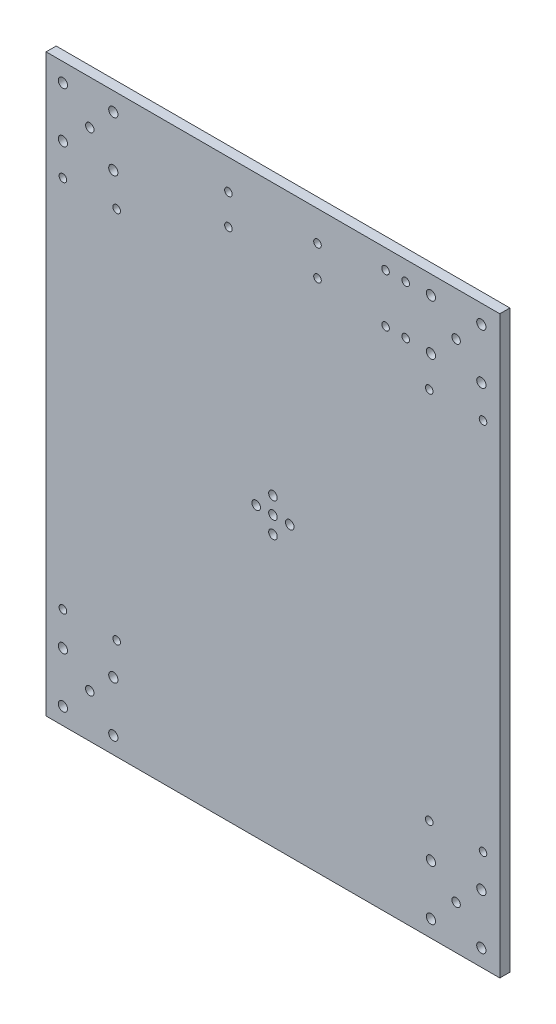
SolidWorks part; units mm, degrees
ref_plane "Спереди" through (0, 0, 0) normal (0, 0, 1) x (1, 0, 0)
ref_plane "Сверху" through (0, 0, 0) normal (0, 1, 0) x (1, 0, 0)
ref_plane "Справа" through (0, 0, 0) normal (1, 0, 0) x (0, 0, -1)
sketch "Эскиз3" plane through (0, 0, 0) normal (0, 0, 1) x (1, 0, 0)
  line L0 (0, 0) -> (0, 10) construction
  line L5 (135, -171.15) -> (-135, -171.15)
  line L6 (135, -171.15) -> (135, 171.15)
  line L7 (135, 171.15) -> (-135, 171.15)
  line L8 (-135, -171.15) -> (-135, 171.15)
  line L9 (0, 0) -> (10, 0) construction
  line L10 (0, 0) -> (0, -10) construction
  line L11 (0, 0) -> (-10, 0) construction
  line L12 (79, 130.65) -> (79, 159.65) construction
  line L13 (79, 159.65) -> (67, 159.65) construction
  line L14 (67, 159.65) -> (67, 130.65) construction
  line L15 (67, 130.65) -> (79, 130.65) construction
  circle A0 centre (0, 0) radius 2.55
  circle A1 centre (0, 10) radius 2.55
  circle A2 centre (10, 0) radius 2.55
  circle A3 centre (0, -10) radius 2.55
  circle A4 centre (-10, 0) radius 2.55
  circle A17 centre (67, 159.65) radius 2.25
  circle A18 centre (79, 159.65) radius 2.25
  circle A19 centre (67, 130.65) radius 2.25
  circle A20 centre (79, 130.65) radius 2.25
  point P0 (0, 0)
  point P5 (-135, 0)
  point P6 (0, 171.15)
  point P21 (0, 0)
  dimension "D3" = 5.1
  dimension "D4" = 5.1
  dimension "D7" = 4.5
  dimension "D1" = 342.3
  dimension "D2" = 270
  dimension "D5" = 10
  dimension "Позиция_крепления_Z_X" = 67
  dimension "Позиция_крепления_Z_Y" = 159.65
  dimension "Шаг_крепления_Z_X" = 12
  dimension "Шаг_крепления_Z_Y" = 29
  dimension "D6" = 4
extrude "Бобышка-Вытянуть1" add sketch "Эскиз3" along normal blind 6
sketch "Эскиз4" plane through (0, 0, 6) normal (0, 0, 1) x (1, 0, 0)
  line L0 (135, 171.15) -> (-135, 171.15) construction
  line L1 (-135, 171.15) -> (-135, -171.15) construction
  circle A0 centre (-109, 145.15) radius 2.5
  dimension "D1" = 5
  dimension "D2" = 26
  dimension "D3" = 26
extrude "Вырез-Вытянуть1" cut sketch "Эскиз4" against normal through all contours A0
pattern_linear "Линейный массив1" count 2 spacing 218 along (1, 0, 0) count 2 spacing 290.3 along (0, -1, 0) of "Вырез-Вытянуть1"
sketch "Эскиз7" plane through (0, 0, 0) normal (0, 0, -1) x (-1, 0, 0)
  line L9 (-26.5, 153.15) -> (26.5, 153.15) construction
  line L10 (-26.5, 153.15) -> (-26.5, 135.15) construction
  line L11 (-26.5, 135.15) -> (26.5, 135.15) construction
  line L16 (26.5, 153.15) -> (26.5, 135.15) construction
  line L17 (-135, 171.15) -> (135, 171.15) construction
  circle A0 centre (-26.5, 153.15) radius 2.25
  circle A1 centre (26.5, 153.15) radius 2.25
  circle A2 centre (-26.5, 135.15) radius 2.25
  circle A3 centre (26.5, 135.15) radius 2.25
  point P4 (0, 135.15)
  dimension "D4" = 4.5
  dimension "D5" = 4.5
  dimension "D6" = 4.5
  dimension "D7" = 4.5
  dimension "D1" = 53
  dimension "D2" = 18
  dimension "D3" = 18
extrude "Вырез-Вытянуть2" cut sketch "Эскиз7" against normal through all
sketch "Эскиз8" plane through (0, 0, 0) normal (0, 0, -1) x (-1, 0, 0)
  line L0 (93, 111.15) -> (125, 111.15) construction
  line L8 (135, 171.15) -> (135, -171.15) construction
  line L9 (-135, 171.15) -> (135, 171.15) construction
  circle A4 centre (93, 111.15) radius 2.25
  circle A5 centre (125, 111.15) radius 2.25
  dimension "D3" = 32
  dimension "D4" = 10
  dimension "D5" = 60
  dimension "D1" = 4.5
  dimension "D2" = 4.5
extrude "Вырез-Вытянуть3" cut sketch "Эскиз8" against normal through all
pattern_linear "Линейный массив2" count 2 spacing 222.3 along (0, -1, 0) count 2 spacing 218 along (1, 0, 0) of "Вырез-Вытянуть3"
sketch "Эскиз10" plane through (0, 0, 0) normal (0, 0, -1) x (-1, 0, 0)
  line L0 (-124, 130.15) -> (-94, 130.15) construction
  line L1 (-129, 125.15) -> (-89, 125.15) construction
  line L2 (-129, 125.15) -> (-129, 165.15) construction
  line L3 (-129, 165.15) -> (-89, 165.15) construction
  line L4 (-89, 125.15) -> (-89, 165.15) construction
  line L5 (-129, 125.15) -> (-89, 165.15) construction
  line L6 (-129, 165.15) -> (-89, 125.15) construction
  line L8 (-94, 130.15) -> (-94, 160.15) construction
  line L10 (-94, 160.15) -> (-124, 160.15) construction
  circle A0 centre (-124, 160.15) radius 2.75
  circle A1 centre (-94, 160.15) radius 2.75
  circle A2 centre (-94, 130.15) radius 2.75
  circle A3 centre (-124, 130.15) radius 2.75
  point P0 (-109, 145.15)
  dimension "D2" = 5.5
  dimension "D1" = 40
  dimension "D3" = 30
extrude "Вырез-Вытянуть4" cut sketch "Эскиз10" against normal through all
pattern_linear "Линейный массив3" count 2 spacing 219 along (-1, 0, 0) count 2 spacing 291.3 along (0, -1, 0) of "Вырез-Вытянуть4"
equation "\"Ширина груза\"= 160"
equation "\"Глубина груза\"= 240"
equation "\"Высота груза\"= 160"
equation "\"Ширина ячейки\"= \"Ширина груза\" + 10"
equation "\"Глубина ячейки\"= \"Глубина груза\" + 10"
equation "\"Высота ячейки\"= \"Высота груза\" + 10 + 13"
equation "\"Колво ячеек ширина\"= 2"
equation "\"Колво ячеек высота\"= 2"
equation "\"Толщина стенки\" = \"Толщина тонких панелей\""
equation "\"Крепление дверцы\"= 5 "
equation "\"Ширина рейки\"= \"Толщина шестерни\""
equation "\"Высота рейки\"= 20"
equation "\"Высота пола\" = 2*\"Толщина тонких панелей\""
equation "\"Колво полозьев\"= 5"
equation "\"Отступ рейки\"= 20"
equation "\"Глубина каретки\"= \"Глубина ячейки\" + 30 + \"Мотор Y высота корпуса\" + 20"
equation "\"Длинна рейки\" = (\"Ширина ячейки\"+\"Толщина вертикальных стенок\"+\"Крепление дверцы\")*\"Колво ячеек ширина\"+\"Ширина ячейки выгрузки\"*\"Колво выгрузки\"+\"Толщина вертикальных стенок\"+2*\"Отступ крепления мотора фиксации\"-\"Крепление дверцы\"*\"Колво ячеек ширина\""
equation "\"Отступ шпильки\"= 26"
equation "\"Диаметр шпильки\"= 5"
equation "\"D1@Бобышка-Вытянуть1\" = \"Толщина стенки\""
equation "\"D1@Эскиз4\"= \"Диаметр шпильки\""
equation "\"D2@Эскиз4\"=\"Отступ шпильки\""
equation "\"D3@Эскиз4\"= \"Отступ шпильки\""
equation "\"D2@Эскиз3\"=\"Ширина ячейки\" + \"Ширина пластины\" * 2"
equation "\"D1@Эскиз3\"=\"Глубина каретки\" "
equation "\"D3@Линейный массив1\"=\"Ширина ячейки\"  +\"Ширина пластины\" *2 - \"Отступ шпильки\" * 2"
equation "\"D4@Линейный массив1\"=\"Глубина каретки\" + \"Ширина рейки\" * 2 - \"Отступ шпильки\" * 2 - \"Ширина рейки\" * 2"
equation "\"Длинна шпильки\" = (\"Высота ячейки\"+\"Толщина горизонтальных плит\"+\"Высота пола\")*\"Колво ячеек высота\"+2*(\"Толщина горизонтальных плит\"+\"Отступ рейки\")"
equation "\"Ширина пластины\"= 50  "
equation "\"Высота зона выгрузки\"= \"Высота ячейки\" * 2 + \"Толщина стенки\" * 2"
equation "\"Колво выгрузки\"= 1"
equation "\"Отступ крепления мотора фиксации\" = (\"Ширина пластины\"+20-\"Толщина вертикальных стенок\")/2"
equation "\"Мотор X ширина корпуса\"= 42.3"
equation "\"Мотор X высота корпуса\"= 42.3"
equation "\"Мотор X длина корпуса\"= 40"
equation "\"Мотор X вылет вала\"= 19.8"
equation "\"Мотор Y ширина корпуса\"= 42.3"
equation "\"Мотор Y высота корпуса\"= 42.3"
equation "\"Мотор Y длина корпуса\"= 48"
equation "\"Мотор Y вылет вала\"= 30"
equation "\"Мотор Z ширина корпуса\"= 42"
equation "\"Мотор Z высота корпуса\"= 42"
equation "\"Мотор Z длина корпуса\"= 40"
equation "\"Мотор Z вылет вала\"= 23"
equation "\"Мотор диаметр вала ПРЕДВ\"= 5"
equation "\"Мотор шаг крепления ПРЕДВ\"= 31"
equation "\"Мотор диаметр отверстий ПРЕДВ\"= 3"
equation "\"Мотор глубина отверстий ПРЕДВ\"= 4.5"
equation "\"Мотор диаметр буртика ПРЕДВ\"= 22"
equation "\"Мотор высота буртика ПРЕДВ\"= 2"
equation "\"Мотор диаметр шкива ПРЕДВ\"= 16"
equation "\"Мотор длина шкива ПРЕДВ\"= 12"
equation "\"Мотор отступ шкива ПРЕДВ\"= 5"
equation "\"Мотор X шаг градусов\"= 1.8"
equation "\"Мотор Y шаг градусов\"= 1.8"
equation "\"Мотор Z шаг градусов\"= 1.8"
equation "\"Мотор Y диаметр ротора\"= 25.78"
equation "\"Толщина шестерни\"= 10"
equation "\"Ширина ячейки выгрузки\" = \"Ширина ячейки\"+\"Толщина вертикальных стенок\"+2*\"Отступ крепления мотора фиксации\""
equation "\"D3@Линейный массив2\" = \"Глубина каретки\"-120"
equation "\"D4@Линейный массив2\" = \"Ширина ячейки\"+2*\"Ширина пластины\"-2*\"Отступ шпильки\""
equation "\"Толщина тонких панелей\" = 6"
equation "\"Толщина вертикальных стенок\" = 6"
equation "\"Толщина горизонтальных плит\" = 6"
equation "\"Базовая высота корпуса\"= (\"Высота ячейки\"+\"Толщина тонких панелей\"+\"Высота пола\")*\"Колво ячеек высота\"+6*\"Толщина тонких панелей\"+\"Мотор X ширина корпуса\"+\"Мотор Y ширина корпуса\"+75"
equation "\"Высота корпуса\"= (\"Высота ячейки\"+\"Толщина горизонтальных плит\"+\"Высота пола\")*\"Колво ячеек высота\"+2*\"Толщина горизонтальных плит\"+4*\"Толщина тонких панелей\"+\"Мотор X ширина корпуса\"+\"Мотор Y ширина корпуса\"+75"
equation "\"Смещение центра корпуса\"= (\"Высота корпуса\"-\"Базовая высота корпуса\")/2-(\"Толщина горизонтальных плит\"-\"Толщина тонких панелей\")"
equation "\"Отметка пола\"= -\"Базовая высота корпуса\"/2+\"Толщина тонких панелей\""
equation "\"Отметка потолка\"= \"Отметка пола\"+\"Высота корпуса\"-2*\"Толщина горизонтальных плит\""
equation "\"Отметка верхней полки\"= \"Отметка потолка\"-(28+\"Толщина тонких панелей\")-\"Высота ячейки\"-\"Высота пола\""
equation "\"Отметка нижней полки\"= \"Отметка верхней полки\"-\"Высота ячейки\"-\"Высота пола\"-\"Толщина горизонтальных плит\""
equation "\"Позиция_крепления_Z_X@Эскиз3\" = (\"Ширина ячейки\"+2*\"Ширина пластины\")/2-68"
equation "\"Позиция_крепления_Z_Y@Эскиз3\" = \"Глубина каретки\"/2-11.5"
equation "\"Шаг_крепления_Z_X@Эскиз3\" = 12"
equation "\"Шаг_крепления_Z_Y@Эскиз3\" = 29"
